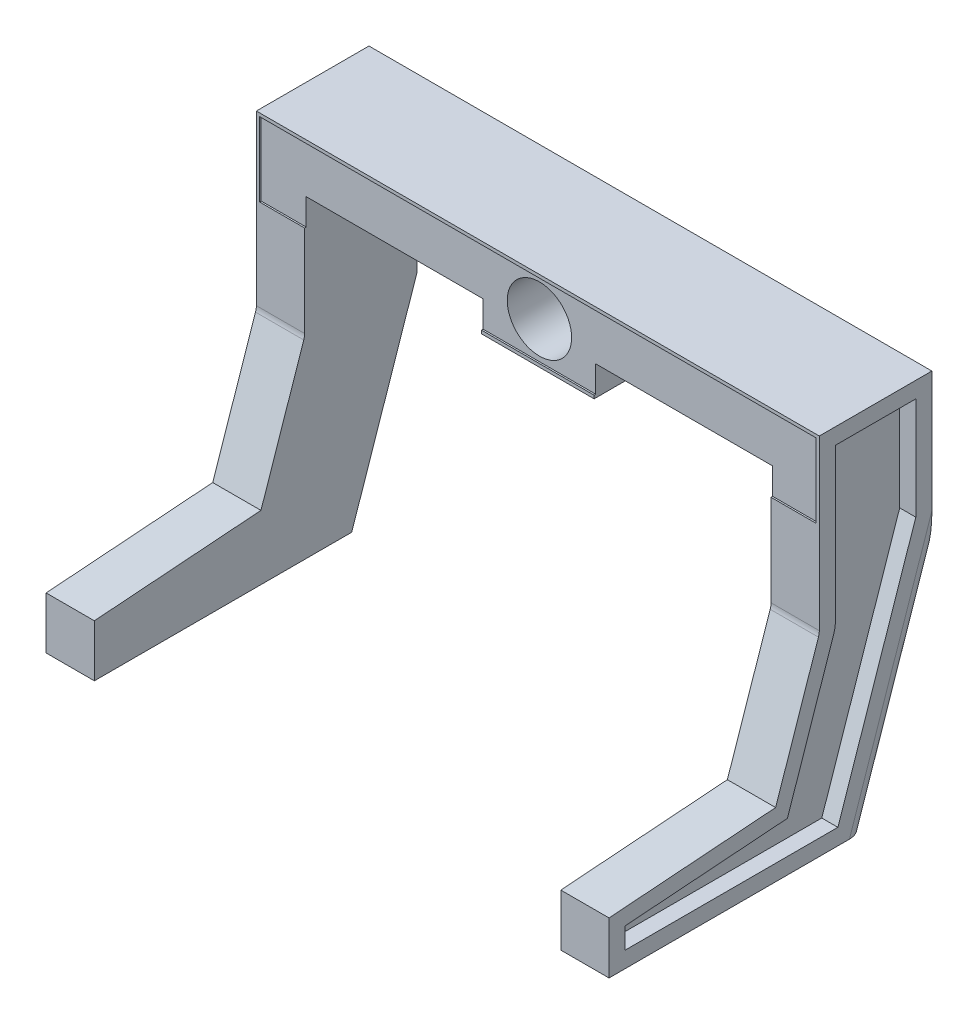
SolidWorks part; units mm, degrees
material "1060 Alloy"
ref_plane "Front Plane" through (0, 0, 0) normal (0, 0, 1) x (1, 0, 0)
ref_plane "Top Plane" through (0, 0, 0) normal (0, 1, 0) x (1, 0, 0)
ref_plane "Right Plane" through (0, 0, 0) normal (1, 0, 0) x (0, 0, -1)
sketch "Sketch1" plane through (0, 0, 0) normal (0, 0, 1) x (1, 0, 0)
  line L0 (-444.5, 0) -> (444.5, 0)
  line L1 (-444.5, 0) -> (-444.5, -127)
  line L2 (-444.5, -127) -> (444.5, -127)
  line L3 (444.5, -127) -> (444.5, 0)
  dimension "D1" = 889
  dimension "D2" = 127
extrude "Boss-Extrude1" add sketch "Sketch1" along normal blind 177.8
sketch "Sketch2" plane through (0, 0, 177.8) normal (0, 0, 1) x (1, 0, 0)
  line L4 (-444.5, -127) -> (444.5, -127) construction
  circle A0 centre (0, -63.5) radius 50.8
  dimension "D1" = 101.6
  dimension "D2" = 63.5
extrude "Cut-Extrude1" cut sketch "Sketch2" against normal through all
sketch "Sketch3" plane through (0, 0, 177.8) normal (0, 0, 1) x (1, 0, 0)
  line L8 (-439.42, -5.08) -> (-439.42, -121.92)
  line L9 (-439.42, -121.92) -> (439.42, -121.92)
  line L10 (439.42, -121.92) -> (439.42, -5.08)
  line L11 (439.42, -5.08) -> (-439.42, -5.08)
  line L12 (-439.42, -5.08) -> (-439.42, -121.92)
  line L13 (-439.42, -121.92) -> (439.42, -121.92)
  line L14 (439.42, -121.92) -> (439.42, -5.08)
  line L15 (439.42, -5.08) -> (-439.42, -5.08)
  circle M5 centre (0, -63.5) radius 50.8
  dimension "D1" = 5.08
extrude "Cut-Extrude2" cut sketch "Sketch3" against normal blind 2.54 contours L14 L15 L12 L13 M5
sketch "Sketch4" plane through (0, 0, 0) normal (0, 0, -1) x (-1, 0, 0)
  line L8 (439.42, -121.92) -> (439.42, -5.08)
  line L9 (439.42, -5.08) -> (-439.42, -5.08)
  line L10 (-439.42, -5.08) -> (-439.42, -121.92)
  line L11 (-439.42, -121.92) -> (439.42, -121.92)
  line L12 (439.42, -121.92) -> (439.42, -5.08)
  line L13 (439.42, -5.08) -> (-439.42, -5.08)
  line L14 (-439.42, -5.08) -> (-439.42, -121.92)
  line L15 (-439.42, -121.92) -> (439.42, -121.92)
  dimension "D1" = 5.08
extrude "Cut-Extrude3" cut sketch "Sketch4" against normal blind 2.54
sketch "Sketch5" plane through (-444.5, 0, 0) normal (-1, 0, 0) x (0, 0, 1)
  line L0 (0, -127) -> (0, -270.4368)
  line L1 (177.8, -127) -> (177.8, -270.4368)
  line L2 (177.8, -270.4368) -> (0, -270.4368)
  line L3 (0, -270.4368) -> (103.456, -575.2368)
  line L5 (177.8, -270.4368) -> (246.7707, -473.6368)
  line L6 (246.7707, -473.6368) -> (509.856, -493.0591)
  line L7 (509.856, -493.0591) -> (509.856, -575.2368)
  line L8 (509.856, -575.2368) -> (103.456, -575.2368)
  line M5 (0, -127) -> (177.8, -127)
  dimension "D1" = 304.8
  dimension "D2" = 203.2
  dimension "D3" = 406.4
extrude "Boss-Extrude2" add sketch "Sketch5" against normal blind 76.2 contours L8 L7 L6 L5 L2 L3 | L2 L1 L0 M5
ref_plane "Plane1" through (444.5, 0, 0) normal (1, 0, 0) x (0, 0, -1)
sketch "Sketch8" plane through (444.5, 0, 0) normal (1, 0, 0) x (0, 0, -1)
  line L44 (-509.856, -575.2368) -> (-103.456, -575.2368)
  line L45 (-509.856, -493.0591) -> (-509.856, -575.2368)
  line L46 (-246.7707, -473.6368) -> (-509.856, -493.0591)
  line L47 (-177.8, -270.4368) -> (-246.7707, -473.6368)
  line L48 (-103.456, -575.2368) -> (0, -270.4368)
  line L49 (0, -270.4368) -> (0, -127)
  line L50 (0, -127) -> (-177.8, -127)
  line L51 (-177.8, -127) -> (-177.8, -270.4368)
  line L52 (-509.856, -575.2368) -> (-103.456, -575.2368)
  line L53 (-509.856, -493.0591) -> (-509.856, -575.2368)
  line L54 (-246.7707, -473.6368) -> (-509.856, -493.0591)
  line L55 (-177.8, -270.4368) -> (-246.7707, -473.6368)
  line L56 (-103.456, -575.2368) -> (0, -270.4368)
  line L57 (0, -270.4368) -> (0, -127)
  line L58 (0, -127) -> (-177.8, -127)
  line L59 (-177.8, -127) -> (-177.8, -270.4368)
  dimension "D1" = 0
extrude "Boss-Extrude3" add sketch "Sketch8" against normal blind 76.2
fillet "Fillet1" radius 25.4 1 edges at (-406.4, -270.4368, 177.8)
fillet "Fillet2" radius 25.4 1 edges at (406.4, -270.4368, 177.8)
fillet "Fillet5" radius 25.4 1 edges at (444.5, -422.8368, 51.728)
fillet "Fillet6" radius 25.4 1 edges at (-444.5, -422.8368, 51.728)
sketch "Sketch10" plane through (444.5, 0, 0) normal (1, 0, 0) x (0, 0, -1)
  line L16 (-484.456, -549.8368) -> (-148.4812, -549.8368)
  line L17 (-148.4812, -549.8368) -> (-25.4, -187.2174)
  line L18 (-25.4, -187.2174) -> (-25.4, -25.4)
  line L19 (-25.4, -25.4) -> (-152.4, -25.4)
  line L20 (-152.4, -25.4) -> (-152.4, -266.2436)
  line L21 (-155.0955, -282.5713) -> (-228.125, -497.7294)
  line L22 (-228.125, -497.7294) -> (-484.456, -516.6531)
  line L23 (-484.456, -516.6531) -> (-484.456, -549.8368)
  line L24 (-484.456, -549.8368) -> (-148.4812, -549.8368)
  line L25 (-148.4812, -549.8368) -> (-25.4, -187.2174)
  line L26 (-25.4, -187.2174) -> (-25.4, -25.4)
  line L27 (-25.4, -25.4) -> (-152.4, -25.4)
  line L28 (-152.4, -25.4) -> (-152.4, -266.2436)
  line L29 (-155.0955, -282.5713) -> (-228.125, -497.7294)
  line L30 (-228.125, -497.7294) -> (-484.456, -516.6531)
  line L31 (-484.456, -516.6531) -> (-484.456, -549.8368)
  arc A2 (-155.0955, -282.5713) -> (-152.4, -266.2436) centre (-203.2, -266.2436) ccw
  arc A3 (-155.0955, -282.5713) -> (-152.4, -266.2436) centre (-203.2, -266.2436) ccw
  dimension "D1" = 25.4
extrude "Cut-Extrude5" cut sketch "Sketch10" against normal blind 25.4
sketch "Sketch11" plane through (-444.5, 0, 0) normal (-1, 0, 0) x (0, 0, 1)
  line L16 (25.4, -25.4) -> (25.4, -187.2174)
  line L17 (25.4, -187.2174) -> (148.4812, -549.8368)
  line L18 (148.4812, -549.8368) -> (484.456, -549.8368)
  line L19 (484.456, -549.8368) -> (484.456, -516.6531)
  line L20 (484.456, -516.6531) -> (228.125, -497.7294)
  line L21 (228.125, -497.7294) -> (155.0955, -282.5713)
  line L22 (152.4, -266.2436) -> (152.4, -25.4)
  line L23 (152.4, -25.4) -> (25.4, -25.4)
  line L24 (25.4, -25.4) -> (25.4, -187.2174)
  line L25 (25.4, -187.2174) -> (148.4812, -549.8368)
  line L26 (148.4812, -549.8368) -> (484.456, -549.8368)
  line L27 (484.456, -549.8368) -> (484.456, -516.6531)
  line L28 (484.456, -516.6531) -> (228.125, -497.7294)
  line L29 (228.125, -497.7294) -> (155.0955, -282.5713)
  line L30 (152.4, -266.2436) -> (152.4, -25.4)
  line L31 (152.4, -25.4) -> (25.4, -25.4)
  arc A2 (152.4, -266.2436) -> (155.0955, -282.5713) centre (203.2, -266.2436) ccw
  arc A3 (152.4, -266.2436) -> (155.0955, -282.5713) centre (203.2, -266.2436) ccw
  dimension "D1" = 25.4
extrude "Cut-Extrude6" cut sketch "Sketch11" against normal blind 25.4
sketch "Sketch12" plane through (0, 0, 175.26) normal (0, 0, 1) x (1, 0, 0)
  line L0 (-368.3, -127) -> (-368.3, -266.2436) construction
  line L1 (-368.3, -207.3396) -> (-88.9, -207.3396)
  line L2 (-368.3, -207.3396) -> (-368.3, -80.3396)
  line L3 (-368.3, -80.3396) -> (-88.9, -80.3396)
  line L4 (-88.9, -207.3396) -> (-88.9, -80.3396)
  line L5 (368.3, -127) -> (368.3, -266.2436) construction
  line L6 (88.9, -207.3396) -> (368.3, -207.3396)
  line L7 (88.9, -207.3396) -> (88.9, -80.3396)
  line L8 (88.9, -80.3396) -> (368.3, -80.3396)
  line L9 (368.3, -207.3396) -> (368.3, -80.3396)
  line M10 (-439.42, -121.92) -> (439.42, -121.92)
  dimension "D1" = 279.4
  dimension "D2" = 127
  dimension "D3" = 279.4
  dimension "D4" = 127
extrude "Cut-Extrude7" cut sketch "Sketch12" against normal through all and the other way blind 25.4 contours L4 L3 L2 M10 | L1 L4 L2 M10 | L9 L8 L7 M10 | L6 L9 L7 M10
